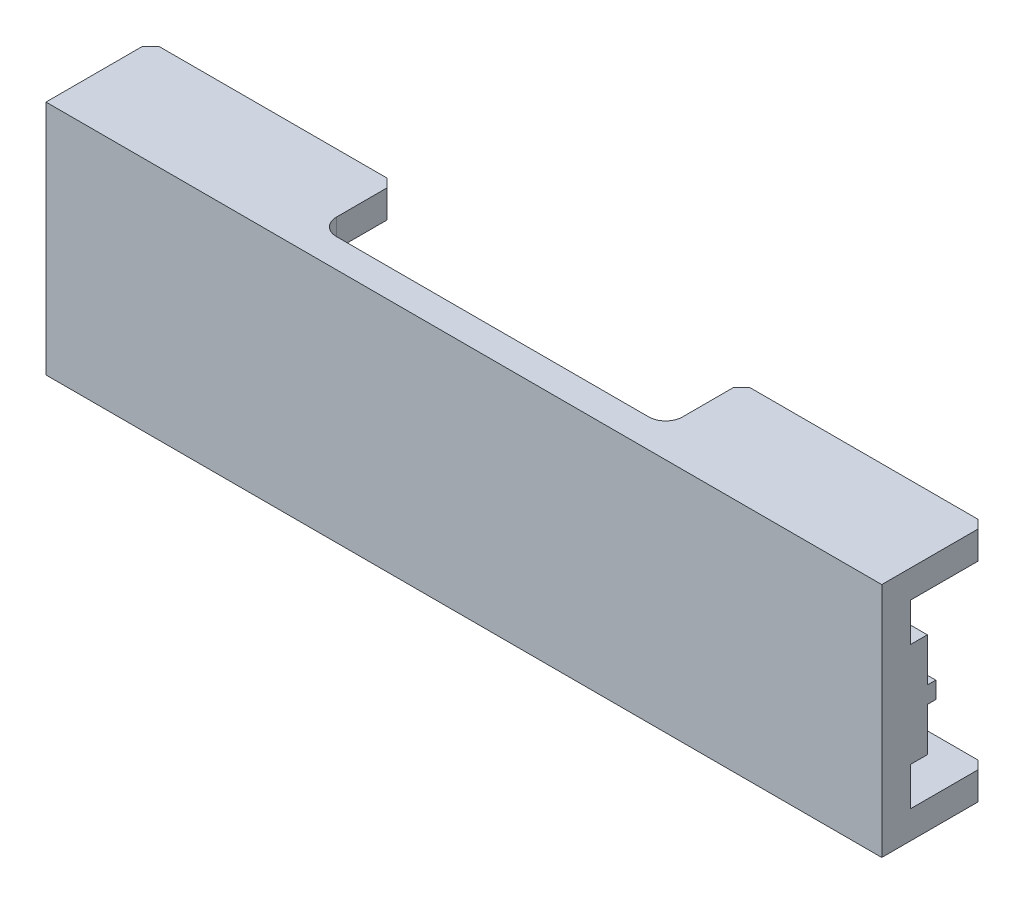
SolidWorks part; units mm, degrees
ref_plane "Front Plane" through (0, 0, 0) normal (0, 0, 1) x (1, 0, 0)
ref_plane "Top Plane" through (0, 0, 0) normal (0, 1, 0) x (1, 0, 0)
ref_plane "Right Plane" through (0, 0, 0) normal (1, 0, 0) x (0, 0, -1)
ref_plane "Plane1" through (0, 10, 0) normal (0, -1, 0) x (-1, 0, 0)
sketch "Sketch1" plane through (0, 0, 0) normal (0, 0, 1) x (1, 0, 0)
  line L0 (25, 24) -> (55, 24) construction
  line L1 (25.5, 24) -> (124.5, 24)
  line L2 (25.5, 24) -> (25.5, -4)
  line L3 (25.5, -4) -> (124.5, -4)
  line L4 (124.5, 24) -> (124.5, -4)
  line L5 (95, -4) -> (125, -4) construction
  line L6 (125, 20.2) -> (125, 24) construction
  line L7 (25, 20.2) -> (25, 24) construction
  dimension "D1" = 0.5
  dimension "D2" = 0.5
extrude "Boss-Extrude1" add sketch "Sketch1" along normal blind 2.5
sketch "Sketch2" plane through (0, -4, 0) normal (0, -1, 0) x (1, 0, 0)
  line L0 (55, -4.5) -> (55, -9.5) construction
  line L1 (25.5, 0) -> (54.5, 0)
  line L2 (25.5, 0) -> (25.5, -7)
  line L3 (25.5, -7) -> (54.5, -7)
  line L4 (54.5, 0) -> (54.5, -7)
  line L5 (0, -7) -> (150, -7) construction
  line L6 (75, 2.5) -> (75, -12) construction
  line L7 (25.5, 2.5) -> (124.5, 2.5) construction
  line L8 (-15, -12) -> (165, -12) construction
  line L9 (95.5, 0) -> (95.5, -7)
  line L10 (124.5, -7) -> (95.5, -7)
  line L11 (124.5, 0) -> (124.5, -7)
  line L12 (124.5, 0) -> (95.5, 0)
  dimension "D1" = 0.5
extrude "Boss-Extrude2" add sketch "Sketch2" against normal offset from surface (3.3 mm away) 0.5
fillet "Fillet1" radius 2 2 edges at (54.5, -2.35, 0) (95.5, -2.35, 0)
sketch "Sketch5" plane through (0, 0, 0) normal (0, 0, -1) x (-1, 0, 0)
  line L0 (-124.5, -0.7) -> (-124.5, 24) construction
  line L1 (-124.5, 16.15) -> (-25.5, 16.15)
  line L2 (-124.5, 16.15) -> (-124.5, 7.15)
  line L3 (-124.5, 7.15) -> (-25.5, 7.15)
  line L4 (-25.5, 16.15) -> (-25.5, 7.15)
  line L5 (-25.5, 24) -> (-25.5, -0.7) construction
  point P9 (-124.5, 11.65)
  point P10 (-124.5, 11.65)
  dimension "D1" = 9
extrude "Boss-Extrude3" add sketch "Sketch5" along normal blind 2
other "Move Face2" face at (40, -2.35, -7) face at (110, -2.35, -7) parameters "D1"=2
chamfer "Chamfer1" distance 1 angle 45 4 edges at (54.5, -2.35, -9) (95.5, -2.35, -9) (124.5, -2.35, -9) (25.5, -2.35, -9)
mirror "Mirror1" about plane through (0, 10, 0) normal (0, -1, 0) of bodies 108 102
sketch "Sketch6" plane through (0, 0, -2) normal (0, 0, -1) x (-1, 0, 0)
  line L0 (-124.5, 16.15) -> (-124.5, 3.85) construction
  line L1 (-124.5, 9) -> (-25.5, 9)
  line L2 (-124.5, 9) -> (-124.5, 11)
  line L3 (-124.5, 11) -> (-25.5, 11)
  line L4 (-25.5, 9) -> (-25.5, 11)
  line L5 (-25.5, 3.85) -> (-25.5, 16.15) construction
  point P8 (-25.5, 10)
  point P9 (-25.5, 10)
  dimension "D1" = 2
extrude "Boss-Extrude4" add sketch "Sketch6" along normal blind 1
other "Move Face3" face at (75, 10, 2.5) parameters "D1"=0.9
equation "\"offset\"= 2mm"
